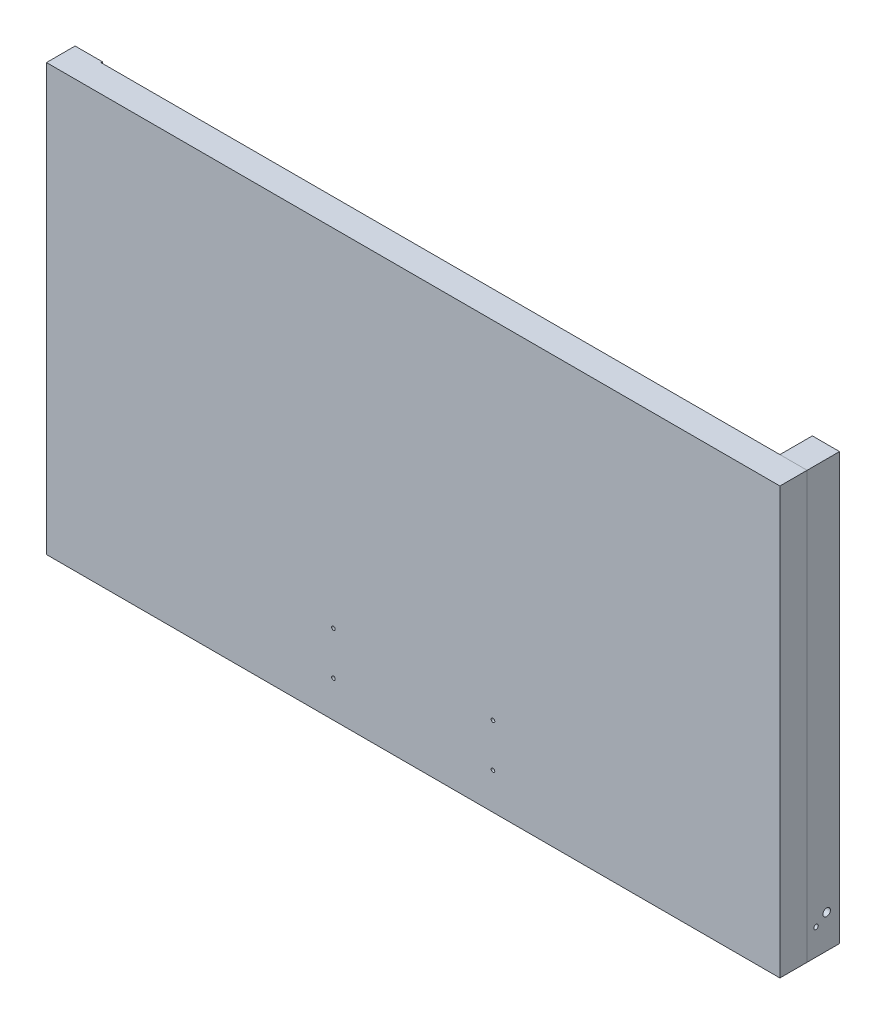
SolidWorks part; units mm, degrees
ref_plane "Alzado" through (0, 0, 0) normal (0, 0, 1) x (1, 0, 0)
ref_plane "Planta" through (0, 0, 0) normal (0, 1, 0) x (1, 0, 0)
ref_plane "Vista lateral" through (0, 0, 0) normal (1, 0, 0) x (0, 0, -1)
sketch "Croquis1" plane through (0, 0, 0) normal (0, 0, 1) x (1, 0, 0)
  line L1 (0, 0) -> (509.67, 0)
  line L2 (0, 0) -> (0, 296.1)
  line L3 (0, 296.1) -> (509.67, 296.1)
  line L4 (509.67, 0) -> (509.67, 296.1)
  dimension "D1" = 296.1
  dimension "D2" = 509.67
extrude "Saliente-Extruir1" add sketch "Croquis1" along normal blind 18.9
sketch "Croquis3" plane through (509.67, 0, 0) normal (1, 0, 0) x (0, 0, -1)
  line L1 (0, 296.1) -> (22.5375, 296.1)
  line L2 (0, 296.1) -> (0, 0)
  line L3 (0, 0) -> (22.5375, 0)
  line L4 (22.5375, 296.1) -> (22.5375, 0)
  circle A4 centre (6.1959, 18.1538) radius 1.575
  circle A5 centre (13.5682, 23.3159) radius 2.6
extrude "Saliente-Extruir2" add sketch "Croquis3" against normal blind 18.9 separate body
sketch "Croquis4" plane through (0, 0, 0) normal (-1, 0, 0) x (0, 0, 1)
  line L1 (0, 296.1) -> (-22.5375, 296.1)
  line L2 (0, 296.1) -> (0, 0)
  line L3 (0, 0) -> (-22.5375, 0)
  line L4 (-22.5375, 296.1) -> (-22.5375, 0)
  circle A0 centre (-20.9403, 28.4783) radius 2.6
  circle A1 centre (-13.5679, 23.3161) radius 1.575
sketch "Croquis9" plane through (0, 0, 0) normal (0, 0, -1) x (-1, 0, 0)
  line L1 (-509.67, 296.1) -> (0, 296.1) construction
  line L2 (-18.9, 296.1) -> (0, 296.1)
  line L3 (-18.9, 296.1) -> (-18.9, 0)
  line L4 (-18.9, 0) -> (0, 0)
  line L5 (0, 296.1) -> (0, 0)
  line L6 (0, 0) -> (-509.67, 0) construction
  line L7 (0, 296.1) -> (0, 0) construction
  dimension "D1" = 18.9
extrude "Saliente-Extruir6" add sketch "Croquis9" along normal blind 1
sketch "Croquis10" plane through (0, 0, 0) normal (-1, 0, 0) x (0, 0, 1)
  circle A0 centre (-20.9426, 28.4831) radius 2.5
  circle A1 centre (-13.5702, 23.3209) radius 1.5
sketch "Croquis11" plane through (0, 0, 18.9) normal (0, 0, 1) x (1, 0, 0)
  line L0 (254.835, -703.9) -> (254.835, 49296.1) construction
  line L4 (0, 296.1) -> (0, 0)
  line L5 (0, 0) -> (509.67, 0)
  line L6 (509.67, 0) -> (509.67, 296.1)
  line L7 (509.67, 296.1) -> (0, 296.1)
  line L8 (0, 296.1) -> (0, 0)
  line L9 (0, 0) -> (509.67, 0)
  line L10 (509.67, 0) -> (509.67, 296.1)
  line L11 (509.67, 296.1) -> (0, 296.1)
  circle A0 centre (310.28, 55.3497) radius 1.265
  circle A1 centre (310.28, 25.3497) radius 1.265
  circle A2 centre (199.39, 25.3497) radius 1.265
  circle A3 centre (199.39, 55.3497) radius 1.265
  point P7 (254.835, 296.1)
  dimension "D2" = 2.53
  dimension "D3" = 2.53
  dimension "D1" = 0
extrude "Cortar-Extruir2" cut sketch "Croquis11" against normal through all contours A1 | A0 | A3 | A2
